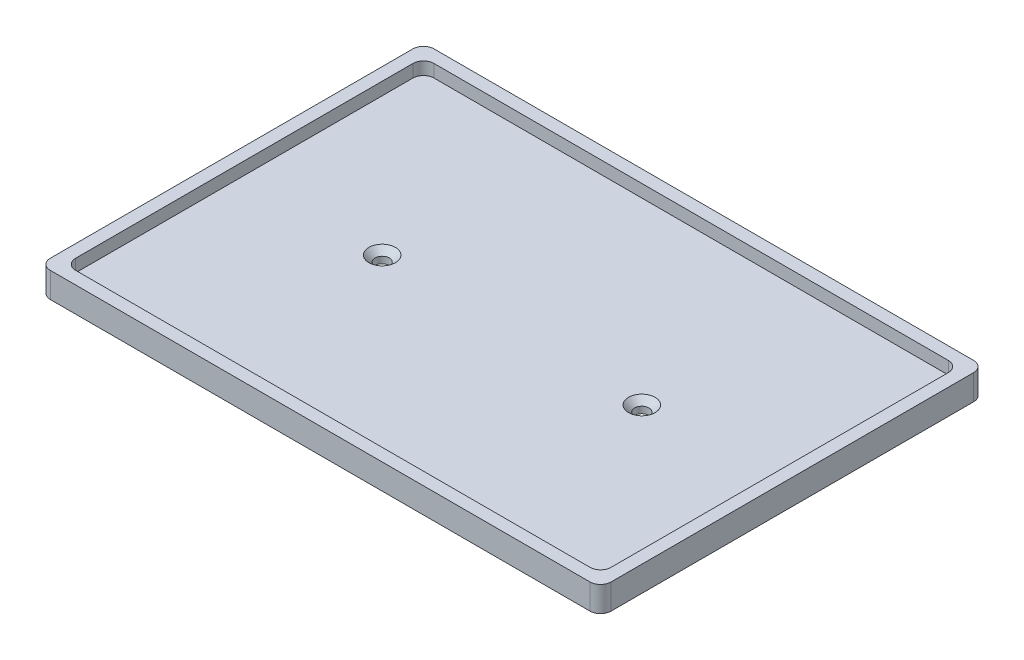
SolidWorks part; units mm, degrees
ref_plane "Front Plane" through (0, 0, 0) normal (0, 0, 1) x (1, 0, 0)
ref_plane "Top Plane" through (0, 0, 0) normal (0, 1, 0) x (1, 0, 0)
ref_plane "Right Plane" through (0, 0, 0) normal (1, 0, 0) x (0, 0, -1)
sketch "Sketch1" plane through (0, 0, 0) normal (0, 1, 0) x (1, 0, 0)
  line L1 (-66.5, 45.5) -> (66.5, 45.5)
  line L2 (-66.5, 45.5) -> (-66.5, -45.5)
  line L3 (-66.5, -45.5) -> (66.5, -45.5)
  line L4 (66.5, 45.5) -> (66.5, -45.5)
  line L5 (-66.5, 45.5) -> (66.5, -45.5) construction
  line L6 (-66.5, -45.5) -> (66.5, 45.5) construction
  point P0 (0, 0)
  dimension "D1" = 91
  dimension "D2" = 133
extrude "Boss-Extrude1" add sketch "Sketch1" along normal blind 6
sketch "Sketch2" plane through (0, 6, 0) normal (0, 1, 0) x (1, 0, 0)
  line L1 (-63.5, 42.5) -> (63.5, 42.5)
  line L2 (-63.5, 42.5) -> (-63.5, -42.5)
  line L3 (-63.5, -42.5) -> (63.5, -42.5)
  line L4 (63.5, 42.5) -> (63.5, -42.5)
  line L5 (-63.5, 42.5) -> (63.5, -42.5) construction
  line L6 (-63.5, -42.5) -> (63.5, 42.5) construction
  point P0 (0, 0)
  dimension "D1" = 85
  dimension "D2" = 127
extrude "Cut-Extrude1" cut sketch "Sketch2" against normal blind 3
fillet "Fillet1" radius 2.5 8 edges at (66.5, 3, -45.5) (63.5, 4.5, -42.5) (63.5, 4.5, 42.5) (-63.5, 4.5, 42.5) (-66.5, 3, -45.5) (-63.5, 4.5, -42.5) (66.5, 3, 45.5) (-66.5, 3, 45.5)
hole_wizard "CSK for M3 Flat Head Machine Screw1" positions "Sketch3" profile "Sketch4" countersink size "M3" standard "ANSI Metric"
sketch "Sketch3" plane through (0, 3, 0) normal (0, 1, 0) x (1, 0, 0)
  line L0 (30.8, 0) -> (-30.8, 0) construction
  point P0 (-30.8, 0)
  point P2 (30.8, 0)
  point P11 (0, 0)
  dimension "D1" = 61.6
sketch "Sketch4" plane through (-30.8, 3, 0) normal (1, 0, 0) x (0, 0, 1)
  line L0 (0, 0) -> (0, 18.4015)
  line L1 (0, 18.4015) -> (1.7, 17.38)
  line L2 (1.7, 17.38) -> (1.7, 1.45)
  line L3 (1.7, 1.45) -> (3.15, 0)
  line L5 (3.15, 0) -> (0, 0)
  line L6 (-1.7, 1.45) -> (-3.15, 0) construction
  line L10 (0, 18.4015) -> (-1.7, 17.38) construction
  line L11 (0, -6.35) -> (0, 107.95) construction
  dimension "Hole Dia." = 3.4
  dimension "Hole Depth" = 17.38
  dimension "Near C'Sink Dia." = 6.3
  dimension "Near C'Sink Angle" = 90
  dimension "Drill Angle" = 118
